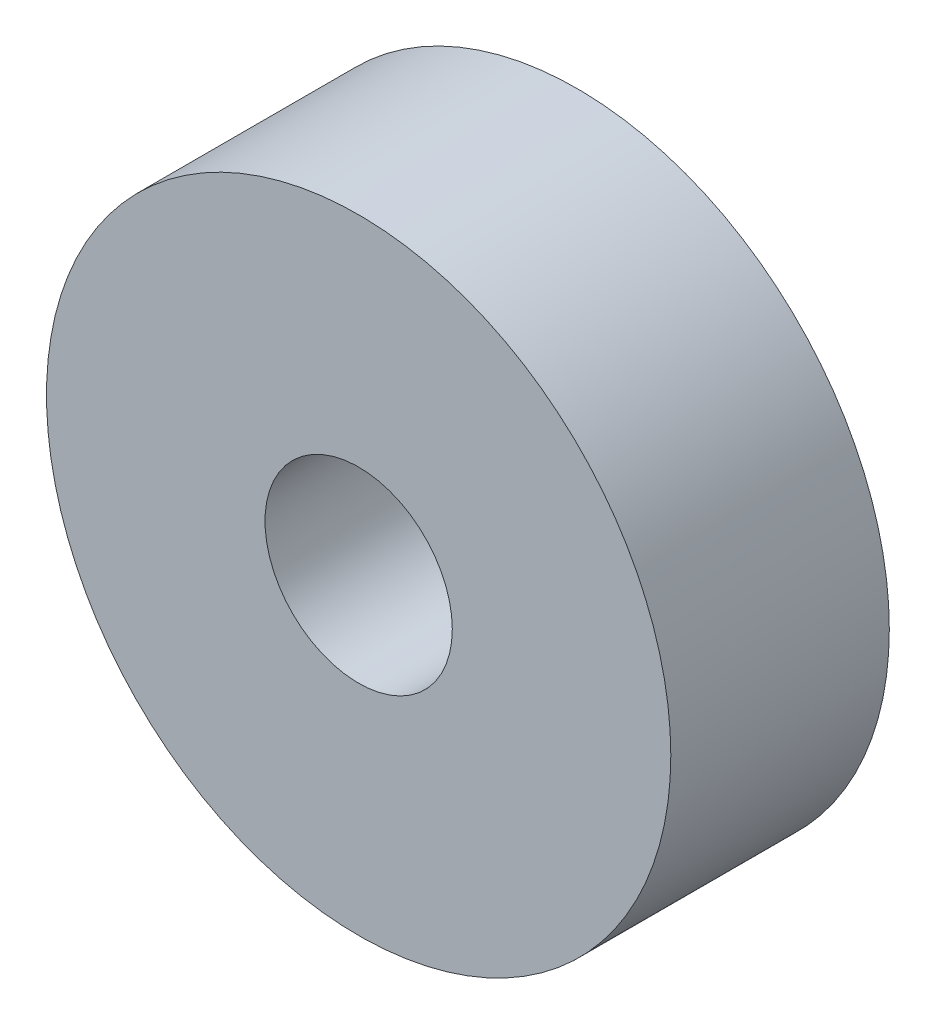
SolidWorks part; units mm, degrees
ref_plane "Front Plane" through (0, 0, 0) normal (0, 0, 1) x (1, 0, 0)
ref_plane "Top Plane" through (0, 0, 0) normal (0, 1, 0) x (1, 0, 0)
ref_plane "Right Plane" through (0, 0, 0) normal (1, 0, 0) x (0, 0, -1)
sketch "Sketch1" plane through (0, 0, 0) normal (0, 0, 1) x (1, 0, 0)
  circle A0 centre (-60.068, 2.9445) radius 175
  circle A1 centre (-60.068, 2.9445) radius 30
sketch "Sketch2" plane through (0, 0, 0) normal (0, 0, 1) x (1, 0, 0)
  circle A0 centre (-60.068, 2.9445) radius 100
  circle A1 centre (-60.068, 2.9445) radius 30
extrude "Boss-Extrude1" add sketch "Sketch2" along normal blind 70
